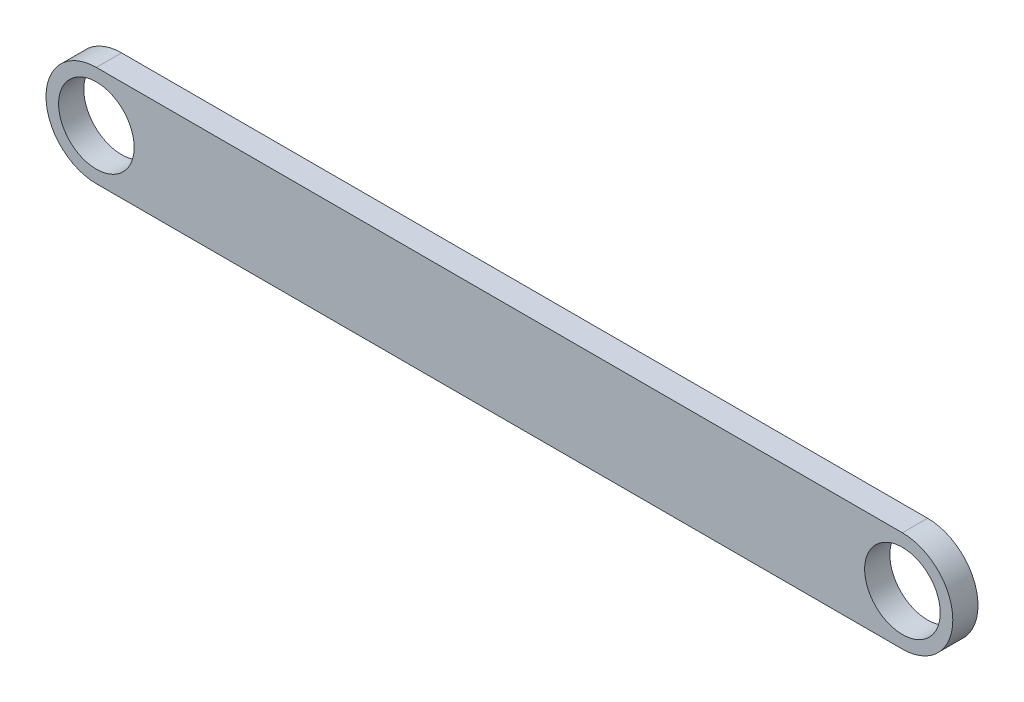
SolidWorks part; units mm, degrees
ref_plane "Спереди" through (0, 0, 0) normal (0, 0, 1) x (1, 0, 0)
ref_plane "Сверху" through (0, 0, 0) normal (0, 1, 0) x (1, 0, 0)
ref_plane "Справа" through (0, 0, 0) normal (1, 0, 0) x (0, 0, -1)
other "Configuration Table"
sketch "Эскиз1" plane through (0, 0, 0) normal (0, 0, 1) x (1, 0, 0)
  line L0 (0, 0) -> (320, 0) construction
  line L1 (0, 20) -> (320, 20)
  line L2 (0, -20) -> (320, -20)
  arc A0 (0, 20) -> (0, -20) centre (0, 0) ccw
  arc A1 (320, -20) -> (320, 20) centre (320, 0) ccw
  circle A2 centre (0, 0) radius 15
  circle A3 centre (320, 0) radius 15
  point P3 (160, 0)
  dimension "D1" = 320
  dimension "D3" = 30
  dimension "D4" = 30
  dimension "D2" = 40
extrude "Бобышка-Вытянуть1" add sketch "Эскиз1" along normal blind 10
